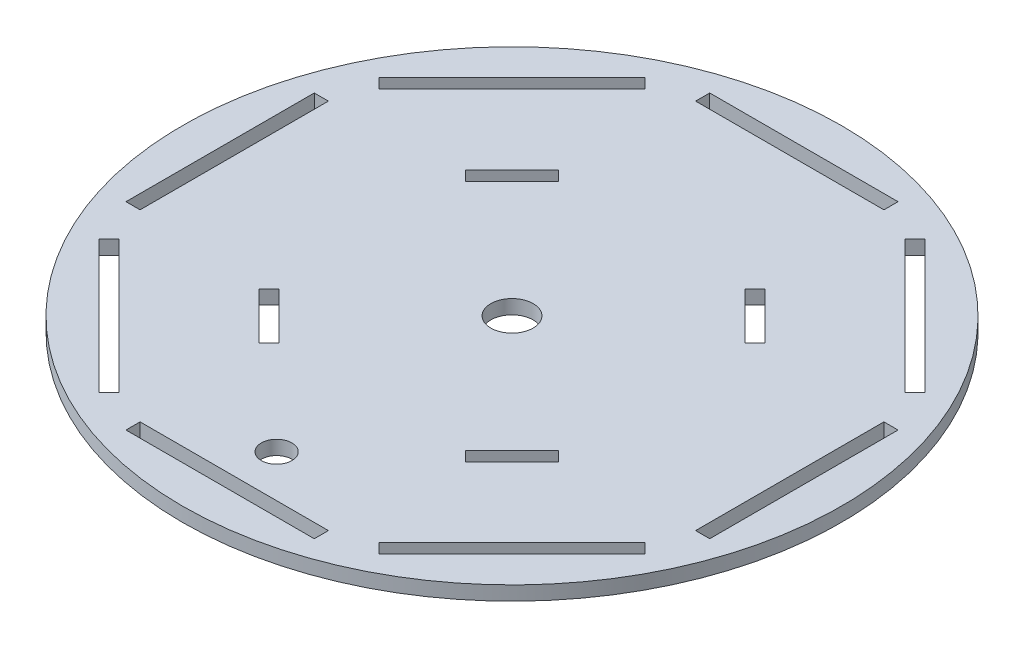
SolidWorks part; units mm, degrees
ref_plane "Alzado" through (0, 0, 0) normal (0, 0, 1) x (1, 0, 0)
ref_plane "Planta" through (0, 0, 0) normal (0, 1, 0) x (1, 0, 0)
ref_plane "Vista lateral" through (0, 0, 0) normal (1, 0, 0) x (0, 0, -1)
sketch "Croquis1" plane through (0, 0, 0) normal (0, 1, 0) x (1, 0, 0)
  line L0 (24.7487, 24.7487) -> (29.6985, 19.799)
  line L1 (29.6985, 19.799) -> (31.8198, 21.9203)
  line L2 (31.8198, 21.9203) -> (21.9203, 31.8198)
  line L3 (19.799, 29.6985) -> (21.9203, 31.8198)
  line L4 (24.7487, 24.7487) -> (19.799, 29.6985)
  line L5 (24.7487, -24.7487) -> (19.799, -29.6985)
  line L6 (19.799, -29.6985) -> (21.9203, -31.8198)
  line L7 (21.9203, -31.8198) -> (31.8198, -21.9203)
  line L8 (29.6985, -19.799) -> (31.8198, -21.9203)
  line L9 (24.7487, -24.7487) -> (29.6985, -19.799)
  line L10 (0, 0) -> (-24.7487, 24.7487) construction
  line L11 (-24.7487, 24.7487) -> (-19.799, 29.6985)
  line L12 (-19.799, 29.6985) -> (-21.9203, 31.8198)
  line L13 (-24.7487, -24.7487) -> (-29.6985, -19.799)
  line L14 (-29.6985, -19.799) -> (-31.8198, -21.9203)
  line L15 (-31.8198, -21.9203) -> (-21.9203, -31.8198)
  line L16 (-19.799, -29.6985) -> (-21.9203, -31.8198)
  line L17 (-24.7487, -24.7487) -> (-19.799, -29.6985)
  line L18 (0, 0) -> (0, -50) construction
  line L23 (-21.9203, 31.8198) -> (-31.8198, 21.9203)
  line L24 (-24.7487, 24.7487) -> (-29.6985, 19.799)
  line L25 (-29.6985, 19.799) -> (-31.8198, 21.9203)
  line L41 (0, 0) -> (0, 62) construction
  line L42 (0, 62) -> (20, 62)
  line L43 (20, 62) -> (20, 59)
  line L44 (20, 59) -> (-20, 59)
  line L45 (-20, 59) -> (-20, 62)
  line L46 (-20, 62) -> (0, 62)
  line L47 (55.8614, 27.5772) -> (27.5772, 55.8614)
  line L48 (27.5772, 55.8614) -> (29.6985, 57.9828)
  line L49 (29.6985, 57.9828) -> (43.8406, 43.8406)
  line L50 (43.8406, 43.8406) -> (57.9828, 29.6985)
  line L51 (57.9828, 29.6985) -> (55.8614, 27.5772)
  line L52 (59, -20) -> (59, 20)
  line L53 (59, 20) -> (62, 20)
  line L54 (62, 20) -> (62, 0)
  line L55 (62, 0) -> (62, -20)
  line L56 (62, -20) -> (59, -20)
  line L57 (27.5772, -55.8614) -> (55.8614, -27.5772)
  line L58 (55.8614, -27.5772) -> (57.9828, -29.6985)
  line L59 (57.9828, -29.6985) -> (43.8406, -43.8406)
  line L60 (43.8406, -43.8406) -> (29.6985, -57.9828)
  line L61 (29.6985, -57.9828) -> (27.5772, -55.8614)
  line L62 (-20, -59) -> (20, -59)
  line L63 (20, -59) -> (20, -62)
  line L64 (20, -62) -> (0, -62)
  line L65 (0, -62) -> (-20, -62)
  line L66 (-20, -62) -> (-20, -59)
  line L67 (-55.8614, -27.5772) -> (-27.5772, -55.8614)
  line L68 (-27.5772, -55.8614) -> (-29.6985, -57.9828)
  line L69 (-29.6985, -57.9828) -> (-43.8406, -43.8406)
  line L70 (-43.8406, -43.8406) -> (-57.9828, -29.6985)
  line L71 (-57.9828, -29.6985) -> (-55.8614, -27.5772)
  line L72 (-59, 20) -> (-59, -20)
  line L73 (-59, -20) -> (-62, -20)
  line L74 (-62, -20) -> (-62, 0)
  line L75 (-62, 0) -> (-62, 20)
  line L76 (-62, 20) -> (-59, 20)
  line L77 (-27.5772, 55.8614) -> (-55.8614, 27.5772)
  line L78 (-55.8614, 27.5772) -> (-57.9828, 29.6985)
  line L79 (-57.9828, 29.6985) -> (-43.8406, 43.8406)
  line L80 (-43.8406, 43.8406) -> (-29.6985, 57.9828)
  line L81 (-29.6985, 57.9828) -> (-27.5772, 55.8614)
  circle A0 centre (0, 0) radius 4.5
  circle A1 centre (0, -50) radius 3.25
  circle A2 centre (0, 0) radius 70
  point P26 (0, 0)
  point P47 (0, 0)
  point P88 (0, 0)
  dimension "D2" = 7
  dimension "D3" = 140
  dimension "D7" = 6.5
  dimension "D4" = 35
  dimension "D5" = 4
  dimension "D6" = 50
  dimension "D9" = 7
  dimension "D10" = 3
  dimension "D15" = 20
  dimension "D16" = 3
  dimension "D17" = 40
  dimension "D18" = 8
extrude "Saliente-Extruir1" add sketch "Croquis1" along normal blind 3
